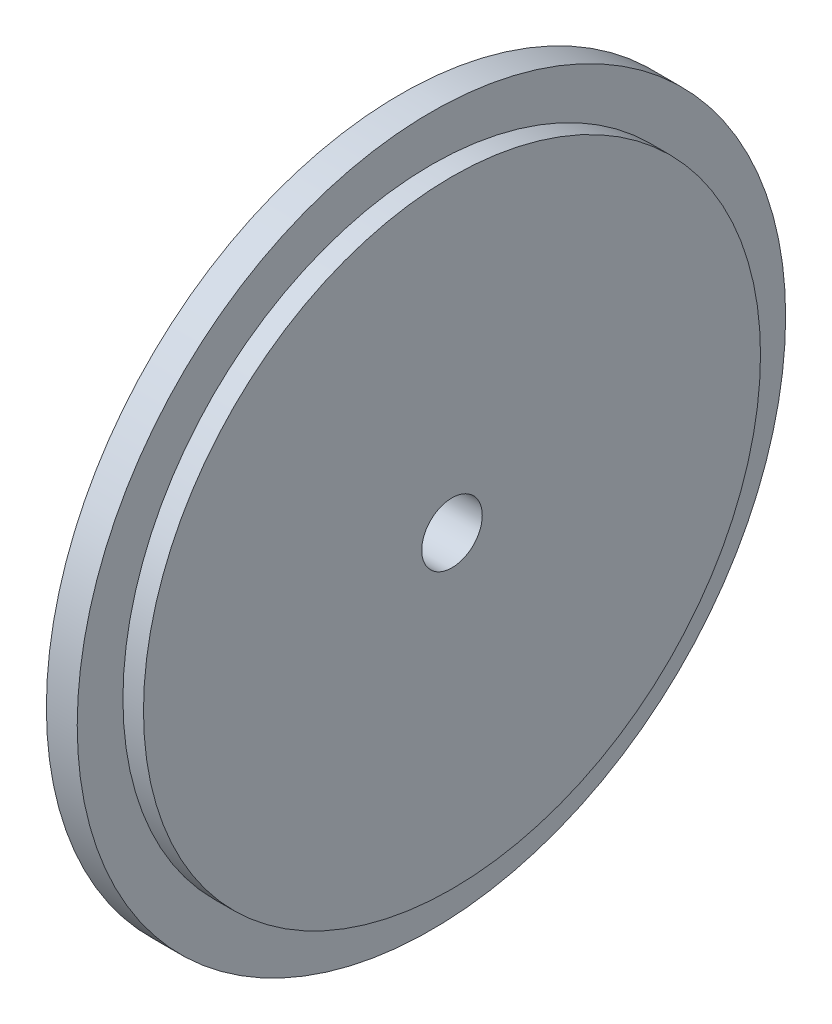
SolidWorks part; units mm, degrees
ref_plane "Front Plane" through (0, 0, 0) normal (0, 0, 1) x (1, 0, 0)
ref_plane "Top Plane" through (0, 0, 0) normal (0, 1, 0) x (1, 0, 0)
ref_plane "Right Plane" through (0, 0, 0) normal (1, 0, 0) x (0, 0, -1)
sketch "Sketch1" plane through (0, 0, 0) normal (1, 0, 0) x (0, 0, -1)
  circle A0 centre (0, 0) radius 31
  circle A1 centre (0, 0) radius 2.65
  dimension "D1" = 62
  dimension "D2" = 5.3
extrude "Boss-Extrude1" add sketch "Sketch1" along normal blind 4.5
sketch "Sketch2" plane through (4.5, 0, 0) normal (1, 0, 0) x (0, 0, -1)
  circle A0 centre (0, 0) radius 27
  circle A2 centre (0, 0) radius 50
  dimension "D1" = 54
  dimension "D2" = 100
extrude "Cut-Extrude1" cut sketch "Sketch2" against normal blind 1.8
